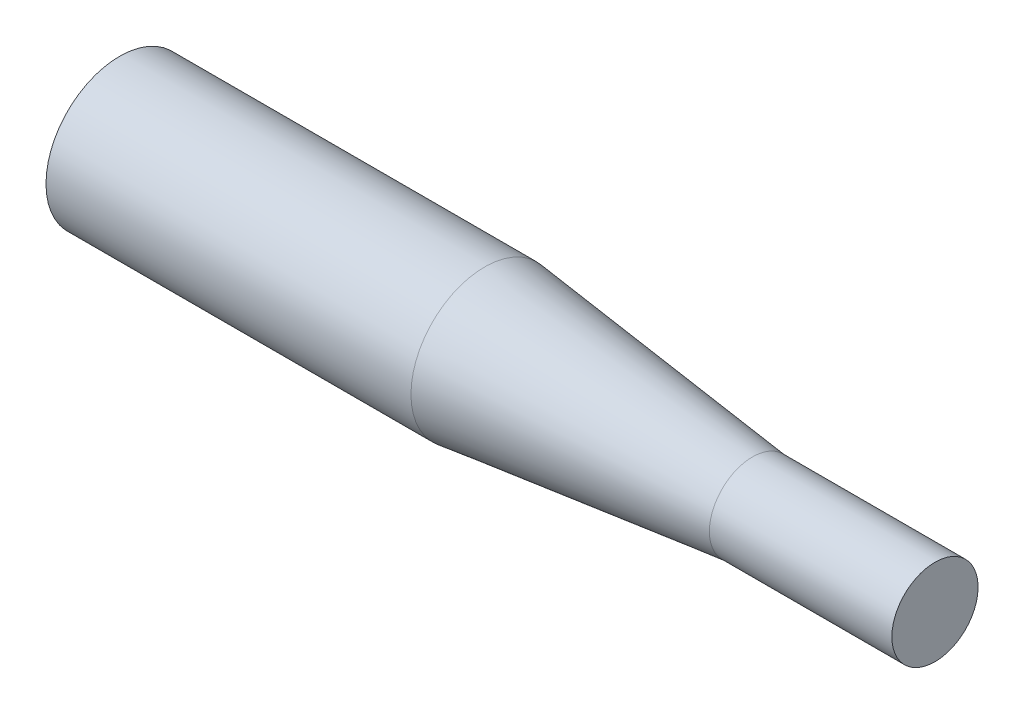
SolidWorks part; units mm, degrees
ref_plane "Front Plane" through (0, 0, 0) normal (0, 0, 1) x (1, 0, 0)
ref_plane "Top Plane" through (0, 0, 0) normal (0, 1, 0) x (1, 0, 0)
ref_plane "Right Plane" through (0, 0, 0) normal (1, 0, 0) x (0, 0, -1)
sketch "Sketch1" plane through (0, 0, 0) normal (0, 1, 0) x (1, 0, 0)
  line L0 (-101.6, 20.4978) -> (0, 20.4978)
  line L1 (0, -55) -> (0, 55) construction
  line L2 (0, 20.4978) -> (74.5842, 12)
  line L3 (74.5842, 12) -> (125.3842, 12)
  line L4 (125.3842, 12) -> (125.3842, 0)
  line L5 (-55, 0) -> (55, 0) construction
  line L6 (125.3842, 0) -> (-101.6, 0)
  line L7 (-101.6, 0) -> (-101.6, 20.4978)
  line L8 (-121.4541, 0) -> (140.8761, 0) construction
  dimension "D1" = 12
  dimension "D2" = 20.4978
  dimension "D3" = 6.5
  dimension "D4" = 101.6
  dimension "D5" = 50.8
revolve "Revolve1" add sketch "Sketch1" angle 360 about L8
